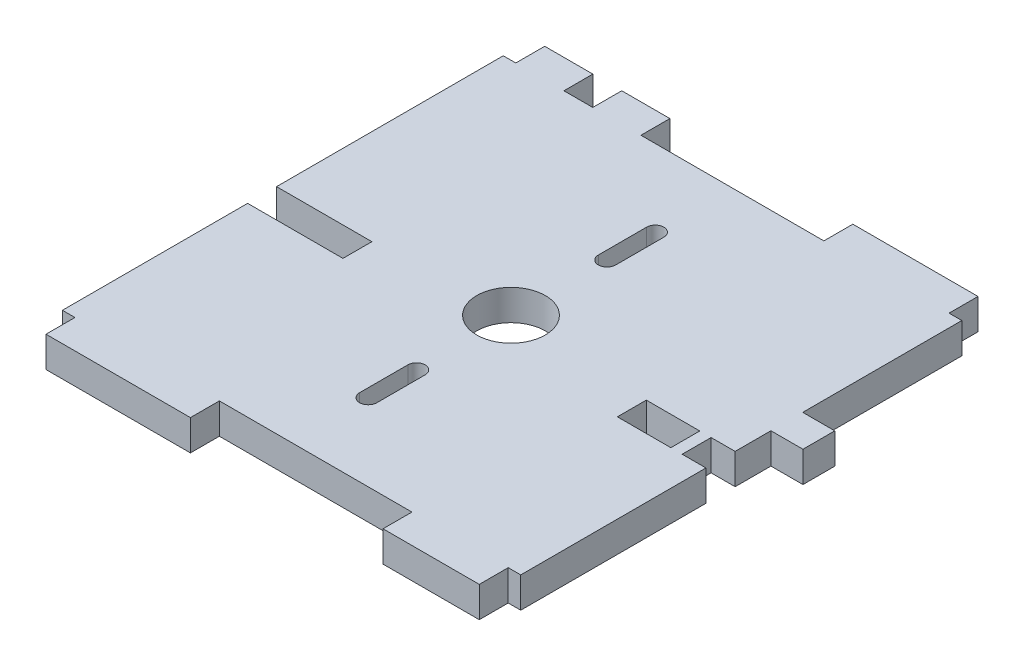
SolidWorks part; units mm, degrees
ref_plane "Front Plane" through (0, 0, 0) normal (0, 0, 1) x (1, 0, 0)
ref_plane "Top Plane" through (0, 0, 0) normal (0, 1, 0) x (1, 0, 0)
ref_plane "Right Plane" through (0, 0, 0) normal (1, 0, 0) x (0, 0, -1)
sketch "Sketch1" plane through (0, 0, 0) normal (0, 1, 0) x (1, 0, 0)
  line L0 (20.4183, 0.9781) -> (20.4183, -2.022)
  line L1 (21.5946, 0.9781) -> (21.5946, -2.022)
  line L2 (24.0851, 0.9781) -> (24.0851, 4.6873)
  line L3 (-23.4561, 24.4792) -> (-23.4561, 0.9783)
  line L17 (24.0851, 7.9873) -> (24.0851, 24.4791)
  line L18 (24.0851, 24.4791) -> (24.0595, 24.4792)
  line L19 (24.0595, 24.4792) -> (22.762, 24.4792)
  line L20 (22.762, 24.4792) -> (22.762, 27.4792)
  line L21 (22.762, 27.4792) -> (9.7849, 27.4792)
  line L22 (9.7849, 27.4792) -> (9.7849, 24.4792)
  line L23 (9.7849, 24.4792) -> (-9.1815, 24.4792)
  line L24 (-9.1815, 24.4792) -> (-9.1815, 27.4792)
  line L25 (-9.1815, 27.4792) -> (-14.1726, 27.4792)
  line L26 (-14.1726, 27.4792) -> (-14.1726, 24.4792)
  line L27 (-14.1726, 24.4792) -> (-17.1672, 24.4792)
  line L28 (-17.1672, 24.4792) -> (-17.1672, 27.4792)
  line L29 (-17.1672, 27.4792) -> (-22.1583, 27.4792)
  line L30 (-22.1583, 27.4792) -> (-22.1583, 24.4792)
  line L31 (-22.1583, 24.4792) -> (-23.4561, 24.4792)
  line L32 (-23.4561, 0.9783) -> (-13.5732, 0.9783)
  line L33 (-13.5732, 0.9783) -> (-13.5732, -2.0219)
  line L34 (-13.5732, -2.0219) -> (-23.4561, -2.0219)
  line L35 (-23.4561, -2.0219) -> (-23.4561, -21.2226)
  line L36 (-23.4561, -21.2226) -> (-22.1583, -21.2226)
  line L37 (-22.1583, -21.2226) -> (-22.1583, -24.2227)
  line L38 (-22.1583, -24.2227) -> (-7.185, -24.2227)
  line L39 (-7.185, -24.2227) -> (-7.185, -21.2226)
  line L40 (-7.185, -21.2226) -> (12.7796, -21.2226)
  line L41 (12.7796, -21.2226) -> (12.7796, -24.2227)
  line L42 (12.7796, -24.2227) -> (22.762, -24.2227)
  line L43 (22.762, -24.2227) -> (22.762, -21.2226)
  line L44 (22.762, -21.2226) -> (24.0595, -21.2226)
  line L45 (24.0595, -21.2226) -> (24.0595, -2.022)
  line L46 (24.0595, -2.022) -> (21.5946, -2.022)
  line L47 (21.5946, 0.9781) -> (24.0851, 0.9781)
  line L49 (24.0851, 4.6873) -> (27.4056, 4.6873)
  line L50 (27.4056, 4.6873) -> (27.4056, 7.9873)
  line L51 (27.4056, 7.9873) -> (24.0851, 7.9873)
  line L52 (-0.6384, 11.5197) -> (-0.6384, 16.5199)
  line L53 (1.1583, 16.5199) -> (1.1583, 11.5197)
  line L54 (-0.6516, -13.2186) -> (-0.6516, -8.2184)
  line L55 (1.1451, -8.2184) -> (1.1451, -13.2186)
  line L56 (20.4183, -2.022) -> (14.8757, -2.022)
  line L57 (14.8757, -2.022) -> (14.8757, 0.9781)
  line L58 (14.8757, 0.9781) -> (20.4183, 0.9781)
  arc A0 (-0.6516, -8.2184) -> (1.1451, -8.2184) centre (0.2467, -8.2184) cw
  arc A1 (1.1451, -13.2186) -> (-0.6516, -13.2186) centre (0.2467, -13.2186) cw
  arc A2 (1.1583, 16.5199) -> (-0.6384, 16.5199) centre (0.26, 16.5199) ccw
  arc A3 (-0.6384, 11.5197) -> (1.1583, 11.5197) centre (0.26, 11.5197) ccw
  circle A4 centre (0.2466, 1.5819) radius 3.5501
  point P4 (0.2466, 1.5819)
extrude "Boss-Extrude1" add sketch "Sketch1" along normal blind 3.175
